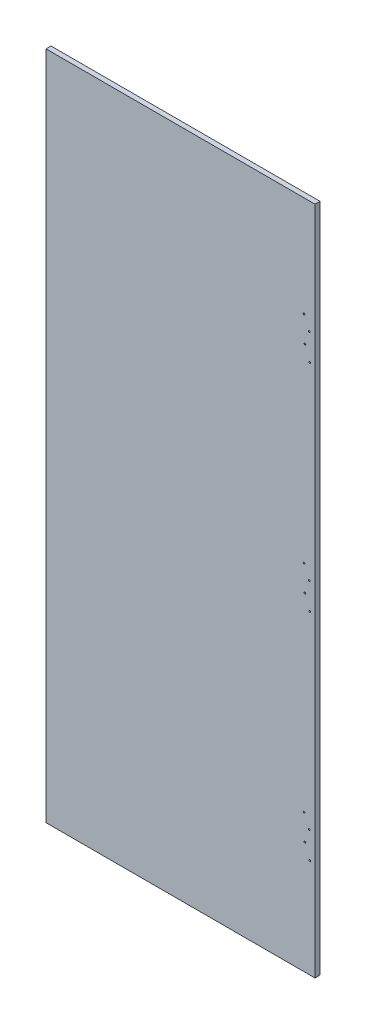
SolidWorks part; units mm, degrees
ref_plane "Front Plane" through (0, 0, 0) normal (0, 0, 1) x (1, 0, 0)
ref_plane "Top Plane" through (0, 0, 0) normal (0, 1, 0) x (1, 0, 0)
ref_plane "Right Plane" through (0, 0, 0) normal (1, 0, 0) x (0, 0, -1)
other "Configuration Table"
sketch "Sketch1" plane through (0, 0, 0) normal (0, 0, 1) x (1, 0, 0)
  line L1 (111.4768, 291.0396) -> (-699.0837, 291.0396)
  line L2 (111.4768, 291.0396) -> (111.4768, -1728.7733)
  line L3 (111.4768, -1728.7733) -> (-699.0837, -1728.7733)
  line L4 (-699.0837, 291.0396) -> (-699.0837, -1728.7733)
extrude "Boss-Extrude1" add sketch "Sketch1" against normal blind 15
sketch "Sketch2" plane through (0, 0, 0) normal (0, 0, 1) x (1, 0, 0)
  circle A0 centre (78.5159, -12.2841) radius 2.6406
  circle A1 centre (94.1632, -49.8171) radius 2.5052
  circle A2 centre (81.1983, -89.2848) radius 2.5527
  circle A3 centre (95.9514, -130.3002) radius 2.5527
  circle A4 centre (78.5159, -662.2841) radius 2.5527
  circle A5 centre (94.1632, -699.8171) radius 2.5527
  circle A6 centre (81.1983, -739.2848) radius 2.5526
  circle A7 centre (95.9514, -780.3002) radius 2.5526
  circle A8 centre (78.5159, -1312.2841) radius 2.5527
  circle A9 centre (94.1632, -1349.8171) radius 2.5526
  circle A10 centre (81.1983, -1389.2848) radius 2.5527
  circle A11 centre (95.9514, -1430.3002) radius 2.5527
extrude "Cut-Extrude1" cut sketch "Sketch2" against normal through all
